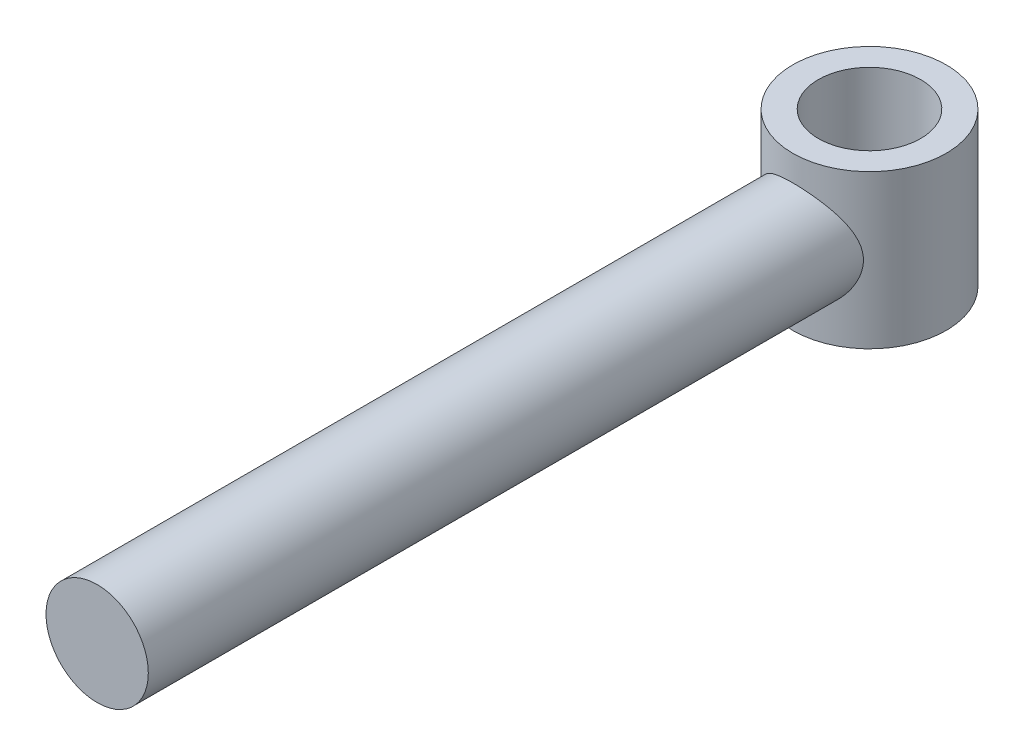
SolidWorks part; units mm, degrees
ref_plane "Front Plane" through (0, 0, 0) normal (0, 0, 1) x (1, 0, 0)
ref_plane "Top Plane" through (0, 0, 0) normal (0, 1, 0) x (1, 0, 0)
ref_plane "Right Plane" through (0, 0, 0) normal (1, 0, 0) x (0, 0, -1)
sketch "Sketch1" plane through (0, 0, 0) normal (0, 0, 1) x (1, 0, 0)
  circle A0 centre (0, 0) radius 12.7
  dimension "D1" = 25.4
extrude "Boss-Extrude1" add sketch "Sketch1" along normal blind 177.8
sketch "Sketch2" plane through (0, 0, 0) normal (0, 1, 0) x (1, 0, 0)
  line L0 (12.7, 0) -> (-12.7, 0) construction
  circle A0 centre (0, 13.97) radius 12.7
  circle A1 centre (0, 13.97) radius 19.05
  point P3 (0, 0)
  dimension "D1" = 25.4
  dimension "D2" = 38.1
  dimension "D3" = 13.97
extrude "Boss-Extrude2" add sketch "Sketch2" along normal mid plane 38.1
